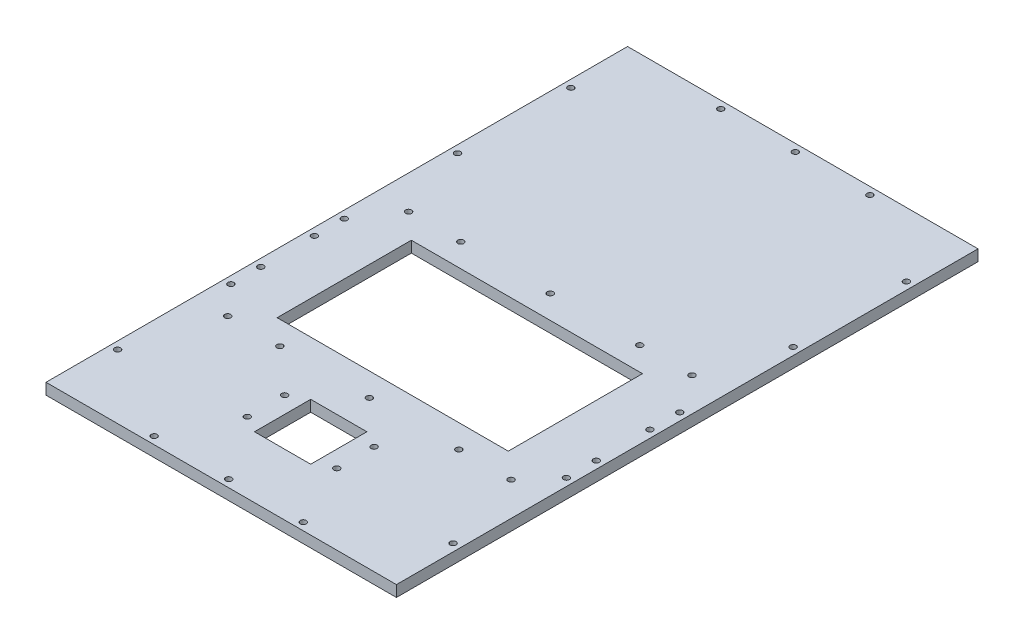
SolidWorks part; units mm, degrees
material "Acrylic (Medium-high impact)"
ref_plane "Front Plane" through (0, 0, 0) normal (0, 0, 1) x (1, 0, 0)
ref_plane "Top Plane" through (0, 0, 0) normal (0, 1, 0) x (1, 0, 0)
ref_plane "Right Plane" through (0, 0, 0) normal (1, 0, 0) x (0, 0, -1)
sketch "Sketch1" plane through (0, 0, 0) normal (0, 1, 0) x (1, 0, 0)
  line L1 (-149.225, -247.65) -> (149.225, -247.65)
  line L2 (-149.225, -247.65) -> (-149.225, 247.65)
  line L3 (-149.225, 247.65) -> (149.225, 247.65)
  line L4 (149.225, -247.65) -> (149.225, 247.65)
  line L5 (-149.225, -247.65) -> (149.225, 247.65) construction
  line L6 (-149.225, 247.65) -> (149.225, -247.65) construction
  line L7 (73.025, -247.65) -> (-130.175, -247.65)
  line L11 (-384.175, -247.65) -> (-231.775, -247.65)
  point P0 (0, 0)
  dimension "D1" = 298.45
  dimension "D2" = 495.3
extrude "Boss-Extrude1" add sketch "Sketch1" along normal mid plane 9.525 contours L1 L4 L3 L2
sketch "Sketch2" [suppressed] plane through (0, 0, 0) normal (0, 1, 0) x (1, 0, 0)
  line L0 (-250.825, -28.575) -> (250.825, -28.575) construction
  line L1 (161.925, -28.575) -> (60.325, -28.575)
  line L2 (161.925, -28.575) -> (161.925, -92.075)
  line L3 (161.925, -92.075) -> (60.325, -92.075)
  line L4 (60.325, -28.575) -> (60.325, -92.075)
  line L5 (0, -5.2388) -> (0, 5.2388) construction
  line L6 (-79.375, -28.575) -> (-168.275, -28.575)
  line L7 (-79.375, -28.575) -> (-79.375, -92.075)
  line L8 (-79.375, -92.075) -> (-168.275, -92.075)
  line L9 (-168.275, -28.575) -> (-168.275, -92.075)
  line L10 (250.825, -28.575) -> (250.825, 28.575) construction
  line L11 (-250.825, -28.575) -> (-250.825, 28.575) construction
  line L12 (-250.825, 28.575) -> (250.825, 28.575) construction
  line L13 (250.825, -28.575) -> (250.825, 28.575) construction
  line L14 (161.925, -28.575) -> (250.825, -28.575)
  line L15 (161.925, -28.575) -> (161.925, -71.755)
  line L16 (161.925, -71.755) -> (250.825, -71.755)
  line L17 (250.825, -28.575) -> (250.825, -71.755)
  line L18 (-250.825, -28.575) -> (-250.825, 28.575) construction
  line L19 (-79.375, -28.575) -> (60.325, -28.575)
  line L20 (-79.375, -28.575) -> (-79.375, -53.975)
  line L21 (-79.375, -53.975) -> (60.325, -53.975)
  line L22 (60.325, -28.575) -> (60.325, -53.975)
  line L23 (-168.275, -28.575) -> (-250.825, -28.575)
  line L24 (-168.275, -28.575) -> (-168.275, -71.755)
  line L25 (-168.275, -71.755) -> (-250.825, -71.755)
  line L26 (-250.825, -28.575) -> (-250.825, -71.755)
  point P19 (60.325, -92.075)
  dimension "D1" = 139.7
  dimension "D2" = 88.9
  dimension "D3" = 82.55
  dimension "D4" = 79.375
  dimension "D5" = 120.65
  dimension "D6" = 43.18
  dimension "D7" = 25.4
  dimension "D8" = 43.18
extrude "Boss-Extrude2" [suppressed] add sketch "Sketch2" along normal mid plane 9.525 contours L6 L9 L8 L7 | L23 L26 L25 L9 | L7 L21 L4 L19 | L17 L14 L2 L16
sketch "Sketch3" plane through (0, 4.7625, 0) normal (0, 1, 0) x (1, 0, 0)
  line L0 (-149.225, 247.65) -> (149.225, 247.65) construction
  line L1 (-98.425, 12.7) -> (98.425, 12.7)
  line L2 (-98.425, 12.7) -> (-98.425, -101.6)
  line L3 (-98.425, -101.6) -> (98.425, -101.6)
  line L4 (98.425, 12.7) -> (98.425, -101.6)
  line L5 (-98.425, 12.7) -> (98.425, -101.6) construction
  line L6 (-98.425, -101.6) -> (98.425, 12.7) construction
  line L7 (-149.225, -247.65) -> (149.225, -247.65) construction
  point P0 (0, -44.45)
  point P7 (0, 247.65)
  point P8 (0, 12.7)
  dimension "D1" = 196.85
  dimension "D2" = 114.3
  dimension "D3" = 203.2
extrude "Cut-Extrude1" cut sketch "Sketch3" against normal through all and the other way through all
sketch "Sketch4" [suppressed] plane through (0, -4.7625, 0) normal (0, -1, 0) x (1, 0, 0)
  line L0 (-107.315, 31.75) -> (107.315, 31.75) construction
  line L1 (-107.315, 33.9979) -> (107.315, 33.9979)
  line L2 (-107.315, 29.5021) -> (107.315, 29.5021)
  line L3 (-107.315, 6.35) -> (107.315, 6.35) construction
  line L4 (-107.315, 8.5979) -> (107.315, 8.5979)
  line L5 (-107.315, 4.1021) -> (107.315, 4.1021)
  arc A0 (-107.315, 33.9979) -> (-107.315, 29.5021) centre (-107.315, 31.75) ccw
  arc A1 (107.315, 29.5021) -> (107.315, 33.9979) centre (107.315, 31.75) ccw
  arc A2 (-107.315, 8.5979) -> (-107.315, 4.1021) centre (-107.315, 6.35) ccw
  arc A3 (107.315, 4.1021) -> (107.315, 8.5979) centre (107.315, 6.35) ccw
  point P0 (-107.315, 31.75)
  point P1 (107.315, 31.75)
  point P3 (107.315, 6.35)
  point P5 (-107.315, 6.35)
  point P10 (0, 31.75)
  point P15 (0, 6.35)
  dimension "D1" = 4.4958
  dimension "D2" = 4.4958
extrude "Cut-Extrude2" [suppressed] cut sketch "Sketch4" against normal through all
sketch "Sketch5" [suppressed] plane through (0, -4.7625, 0) normal (0, -1, 0) x (1, 0, 0)
  line L0 (69.85, 79.375) -> (69.85, -9.525) construction
  line L1 (60.325, 53.975) -> (60.325, 92.075) construction
  line L2 (161.925, 92.075) -> (60.325, 92.075) construction
  line L3 (-247.65, -22.225) -> (247.65, -22.225) construction
  line L4 (69.85, 79.375) -> (69.85, -9.525) construction
  line L5 (72.0979, 79.375) -> (72.0979, -9.525)
  line L6 (67.6021, 79.375) -> (67.6021, -9.525)
  line L7 (-88.9, 79.375) -> (-88.9, -9.525) construction
  line L8 (-79.375, 53.975) -> (-79.375, 92.075) construction
  line L9 (-79.375, 92.075) -> (-168.275, 92.075) construction
  line L10 (-88.9, 79.375) -> (-88.9, -9.525) construction
  line L11 (-86.6521, 79.375) -> (-86.6521, -9.525)
  line L12 (-91.1479, 79.375) -> (-91.1479, -9.525)
  arc A0 (72.0979, 79.375) -> (67.6021, 79.375) centre (69.85, 79.375) ccw
  arc A1 (67.6021, -9.525) -> (72.0979, -9.525) centre (69.85, -9.525) ccw
  arc A2 (-86.6521, 79.375) -> (-91.1479, 79.375) centre (-88.9, 79.375) ccw
  arc A3 (-91.1479, -9.525) -> (-86.6521, -9.525) centre (-88.9, -9.525) ccw
  point P8 (69.85, 34.925)
  point P19 (-88.9, 34.925)
  dimension "D1" = 9.525
  dimension "D2" = 12.7
  dimension "D3" = 12.7
  dimension "D4" = 4.4958
  dimension "D5" = 9.525
  dimension "D6" = 12.7
  dimension "D7" = 12.7
  dimension "D8" = 4.4958
extrude "Cut-Extrude3" [suppressed] cut sketch "Sketch5" against normal through all contours L12 A3 L11 A2 | L6 A1 L5 A0
sketch "Sketch6" [suppressed] plane through (0, 4.7625, 0) normal (0, 1, 0) x (1, 0, 0)
  line L0 (-79.375, -38.1) -> (-79.375, 38.1) construction
  line L1 (-88.9, -50.8) -> (-88.9, 50.8) construction
  line L2 (-88.9, -50.8) -> (88.9, -50.8) construction
  line L3 (-88.9, 50.8) -> (88.9, 50.8) construction
  line L4 (79.375, -38.1) -> (79.375, 38.1) construction
  line L5 (88.9, -50.8) -> (88.9, 50.8) construction
  line L6 (-79.375, -38.1) -> (-79.375, 38.1) construction
  line L7 (-81.6229, -38.1) -> (-81.6229, 38.1)
  line L8 (-77.1271, -38.1) -> (-77.1271, 38.1)
  line L9 (79.375, -38.1) -> (79.375, 38.1) construction
  line L10 (77.1271, -38.1) -> (77.1271, 38.1)
  line L11 (81.6229, -38.1) -> (81.6229, 38.1)
  arc A0 (-81.6229, -38.1) -> (-77.1271, -38.1) centre (-79.375, -38.1) ccw
  arc A1 (-77.1271, 38.1) -> (-81.6229, 38.1) centre (-79.375, 38.1) ccw
  arc A2 (77.1271, -38.1) -> (81.6229, -38.1) centre (79.375, -38.1) ccw
  arc A3 (81.6229, 38.1) -> (77.1271, 38.1) centre (79.375, 38.1) ccw
  point P12 (-79.375, 0)
  point P17 (79.375, 0)
  dimension "D1" = 9.525
  dimension "D2" = 12.7
  dimension "D3" = 12.7
  dimension "D4" = 9.525
  dimension "D5" = 12.7
  dimension "D6" = 12.7
  dimension "D7" = 4.4958
  dimension "D8" = 4.4958
extrude "Cut-Extrude4" [suppressed] cut sketch "Sketch6" against normal through all
sketch "Sketch7" [suppressed] plane through (0, 4.7625, 0) normal (0, 1, 0) x (1, 0, 0)
  point P0 (115.1313, 66.802)
  point P1 (139.827, 42.1063)
  point P3 (-139.827, 42.1063)
  point P5 (-115.1313, 66.802)
hole_wizard "#12 Clearance Hole1" [suppressed] positions "Sketch8" profile "Sketch9" hole size "#12" standard "ANSI Inch"
sketch "Sketch8" plane through (0, 4.7625, 0) normal (0, 1, 0) x (1, 0, 0)
  point P0 (-139.827, 42.1063)
  point P3 (-115.1313, 66.802)
  point P6 (115.1313, 66.802)
  point P9 (139.827, 42.1063)
sketch "Sketch9" plane through (-139.827, 4.7625, -42.1063) normal (1, 0, 0) x (0, 0, 1)
  line L0 (0, 0) -> (0, 18.1964)
  line L1 (0, 18.1964) -> (2.8067, 16.51)
  line L2 (2.8067, 16.51) -> (2.8067, 0)
  line L5 (2.8067, 0) -> (0, 0)
  line L10 (0, 18.1964) -> (-2.8067, 16.51) construction
  line L11 (0, -6.35) -> (0, 107.95) construction
  dimension "Hole Dia." = 5.6134
  dimension "Hole Depth" = 16.51
  dimension "Drill Angle" = 118
sketch "Sketch10" [suppressed] plane through (0, -4.7625, 0) normal (0, -1, 0) x (1, 0, 0)
  point P0 (223.8375, -6.35)
  point P1 (223.8375, 19.05)
  point P3 (-223.8375, 19.05)
  point P5 (-223.8375, -6.35)
hole_wizard "#12 Clearance Hole3" [suppressed] positions "Sketch11" profile "Sketch12" hole size "#12" standard "ANSI Inch"
sketch "Sketch11" plane through (0, -4.7625, 0) normal (0, -1, 0) x (-1, 0, 0)
  point P0 (-223.8375, -19.05)
  point P3 (-223.8375, 6.35)
  point P6 (223.8375, -19.05)
  point P9 (223.8375, 6.35)
sketch "Sketch12" plane through (223.8375, -4.7625, 19.05) normal (1, 0, 0) x (0, 0, -1)
  line L0 (0, 0) -> (0, 18.1964)
  line L1 (0, 18.1964) -> (2.8067, 16.51)
  line L2 (2.8067, 16.51) -> (2.8067, 0)
  line L5 (2.8067, 0) -> (0, 0)
  line L10 (0, 18.1964) -> (-2.8067, 16.51) construction
  line L11 (0, -6.35) -> (0, 107.95) construction
  dimension "Hole Dia." = 5.6134
  dimension "Hole Depth" = 16.51
  dimension "Drill Angle" = 118
sketch "Sketch13" [suppressed] plane through (0, -4.7625, 0) normal (0, -1, 0) x (1, 0, 0)
  point P0 (133.35, -223.8375)
  point P1 (107.95, -223.8375)
  point P3 (-107.95, -223.8375)
  point P5 (-133.35, -223.8375)
  point P7 (133.35, 223.8375)
  point P9 (107.95, 223.8375)
  point P11 (-107.95, 223.8375)
  point P13 (-133.35, 223.8375)
hole_wizard "#12 Clearance Hole2" [suppressed] positions "Sketch14" profile "Sketch15" hole size "#12" standard "ANSI Inch"
sketch "Sketch14" [suppressed] plane through (0, -4.7625, 0) normal (0, -1, 0) x (-1, 0, 0)
  point P0 (107.95, -223.8375)
  point P3 (133.35, -223.8375)
  point P6 (133.35, 223.8375)
  point P9 (107.95, 223.8375)
  point P12 (-133.35, 223.8375)
  point P15 (-107.95, 223.8375)
  point P18 (-133.35, -223.8375)
  point P21 (-107.95, -223.8375)
sketch "Sketch15" plane through (-107.95, -4.7625, 223.8375) normal (1, 0, 0) x (0, 0, -1)
  line L0 (0, 0) -> (0, 18.1964)
  line L1 (0, 18.1964) -> (2.8067, 16.51)
  line L2 (2.8067, 16.51) -> (2.8067, 0)
  line L5 (2.8067, 0) -> (0, 0)
  line L10 (0, 18.1964) -> (-2.8067, 16.51) construction
  line L11 (0, -6.35) -> (0, 107.95) construction
  dimension "Hole Dia." = 5.6134
  dimension "Hole Depth" = 16.51
  dimension "Drill Angle" = 118
sketch "Sketch16" [suppressed] plane through (0, 4.7625, 0) normal (0, 1, 0) x (1, 0, 0)
  line L0 (88.9, -50.8) -> (88.9, 50.8) construction
  line L1 (-88.9, -50.8) -> (-88.9, 50.8) construction
  line L2 (-88.9, -50.8) -> (88.9, -50.8) construction
  point P0 (79.375, -38.1)
  point P1 (-79.375, -38.1)
  dimension "D1" = 9.525
  dimension "D2" = 9.525
  dimension "D3" = 12.7
hole_wizard "#8 Clearance Hole1" [suppressed] positions "Sketch17" profile "Sketch19" hole size "#8" standard "ANSI Inch"
sketch "Sketch17" plane through (0, 4.7625, 0) normal (0, 1, 0) x (1, 0, 0)
  point P0 (79.375, -38.1)
  point P3 (-79.375, -38.1)
sketch "Sketch19" plane through (79.375, 4.7625, 38.1) normal (1, 0, 0) x (0, 0, 1)
  line L0 (0, 0) -> (0, 12.0187)
  line L1 (0, 12.0187) -> (2.2479, 10.668)
  line L2 (2.2479, 10.668) -> (2.2479, 0)
  line L5 (2.2479, 0) -> (0, 0)
  line L10 (0, 12.0187) -> (-2.2479, 10.668) construction
  line L11 (0, -6.35) -> (0, 107.95) construction
  dimension "Hole Dia." = 4.4958
  dimension "Hole Depth" = 10.668
  dimension "Drill Angle" = 118
sketch "Sketch20" plane through (0, -4.7625, 0) normal (0, -1, 0) x (1, 0, 0)
  line L0 (-149.225, 247.65) -> (149.225, 247.65) construction
  line L1 (23.9395, 147.5105) -> (-23.9395, 147.5105)
  line L2 (23.9395, 147.5105) -> (23.9395, 195.3895)
  line L3 (23.9395, 195.3895) -> (-23.9395, 195.3895)
  line L4 (-23.9395, 147.5105) -> (-23.9395, 195.3895)
  line L5 (23.9395, 147.5105) -> (-23.9395, 195.3895) construction
  line L6 (23.9395, 195.3895) -> (-23.9395, 147.5105) construction
  line L8 (38.1, 155.575) -> (-38.1, 155.575) construction
  line L9 (38.1, 155.575) -> (38.1, 187.325) construction
  line L10 (38.1, 187.325) -> (-38.1, 187.325) construction
  line L11 (-38.1, 155.575) -> (-38.1, 187.325) construction
  point P0 (0, 171.45)
  point P7 (0, 247.65)
  point P8 (38.1, 155.575)
  point P9 (38.1, 187.325)
  point P10 (-38.1, 155.575)
  point P11 (-38.1, 187.325)
  point P18 (0, 187.325)
  point P19 (0, 195.3895)
  point P20 (-38.1, 171.45)
  point P21 (-23.9395, 171.45)
  dimension "D1" = 47.879
  dimension "D2" = 47.879
  dimension "D3" = 38.1
  dimension "D4" = 15.875
  dimension "D5" = 76.2
extrude "Cut-Extrude5" cut sketch "Sketch20" against normal through all contours L1 L4 L3 L2
hole_wizard "#10 Clearance Hole1" positions "Sketch21" profile "Sketch22" hole size "#10" standard "ANSI Inch"
sketch "Sketch21" plane through (0, -4.7625, 0) normal (0, -1, 0) x (-1, 0, 0)
  point P0 (-38.1, -155.575)
  point P3 (38.1, -155.575)
  point P6 (38.1, -187.325)
  point P9 (-38.1, -187.325)
sketch "Sketch22" plane through (38.1, -4.7625, 155.575) normal (1, 0, 0) x (0, 0, -1)
  line L0 (0, 0) -> (0, 12.2018)
  line L1 (0, 12.2018) -> (2.5527, 10.668)
  line L2 (2.5527, 10.668) -> (2.5527, 0)
  line L5 (2.5527, 0) -> (0, 0)
  line L10 (0, 12.2018) -> (-2.5527, 10.668) construction
  line L11 (0, -6.35) -> (0, 107.95) construction
  dimension "Hole Dia." = 5.1054
  dimension "Hole Depth" = 10.668
  dimension "Drill Angle" = 118
sketch "Sketch23" [suppressed] plane through (-250.825, 0, 0) normal (-1, 0, 0) x (0, 0, 1)
  line L4 (-28.575, -4.7625) -> (71.755, -4.7625)
  line L5 (71.755, -4.7625) -> (71.755, 4.7625)
  line L6 (71.755, 4.7625) -> (-28.575, 4.7625)
  line L7 (-28.575, 4.7625) -> (-28.575, -4.7625)
  line L8 (-28.575, -4.7625) -> (71.755, -4.7625)
  line L9 (71.755, -4.7625) -> (71.755, 4.7625)
  line L10 (71.755, 4.7625) -> (-28.575, 4.7625)
  line L11 (-28.575, 4.7625) -> (-28.575, -4.7625)
  dimension "D1" = 0
extrude "Boss-Extrude3" [suppressed] add sketch "Sketch23" along normal blind 6.35
mirror "Mirror1" [suppressed] about plane through (0, 0, 0) normal (1, 0, 0)
sketch "Sketch27" [suppressed] plane through (0, 4.7625, 0) normal (0, 1, 0) x (1, 0, 0)
  line L1 (257.175, -71.755) -> (257.175, 28.575) construction
  line L2 (-257.175, 28.575) -> (257.175, 28.575) construction
  point P0 (241.3, 12.7)
  dimension "D1" = 15.875
  dimension "D2" = 15.875
hole_wizard "#10 Clearance Hole2" [suppressed] positions "Sketch28" profile "Sketch30" hole size "#10" standard "ANSI Inch"
sketch "Sketch28" plane through (0, 4.7625, 0) normal (0, 1, 0) x (1, 0, 0)
  point P0 (241.3, 12.7)
sketch "Sketch30" plane through (241.3, 4.7625, -12.7) normal (1, 0, 0) x (0, 0, 1)
  line L0 (0, 0) -> (0, 9.525)
  line L1 (0, 9.525) -> (2.5527, 9.525)
  line L2 (2.5527, 9.525) -> (2.5527, 0)
  line L5 (2.5527, 0) -> (0, 0)
  line L11 (0, -6.35) -> (0, 107.95) construction
  dimension "Thru Hole Dia." = 5.1054
  dimension "Thru Hole Depth" = 9.525
pattern_linear "LPattern1" [suppressed] count 6 spacing 96.52
sketch "Sketch31" [suppressed] plane through (0, 4.7625, 0) normal (0, 1, 0) x (1, 0, 0)
  line L1 (0, -5.2388) -> (0, 5.2388) construction
  line L2 (-149.225, 76.2) -> (149.225, 76.2) construction
  point P0 (-95.25, 60.325)
  dimension "D1" = 15.875
  dimension "D2" = 95.25
hole_wizard "#10 Clearance Hole3" [suppressed] positions "Sketch32" profile "Sketch33" hole size "#10" standard "ANSI Inch"
sketch "Sketch32" plane through (0, 4.7625, 0) normal (0, 1, 0) x (1, 0, 0)
  point P0 (-95.25, 60.325)
sketch "Sketch33" plane through (-95.25, 4.7625, -60.325) normal (1, 0, 0) x (0, 0, 1)
  line L0 (0, 0) -> (0, 9.525)
  line L1 (0, 9.525) -> (2.5527, 9.525)
  line L2 (2.5527, 9.525) -> (2.5527, 0)
  line L5 (2.5527, 0) -> (0, 0)
  line L11 (0, -6.35) -> (0, 107.95) construction
  dimension "Thru Hole Dia." = 5.1054
  dimension "Thru Hole Depth" = 9.525
pattern_linear "LPattern2" [suppressed] count 4 spacing 63.5
sketch "Sketch34" plane through (0, 4.7625, 0) normal (0, 1, 0) x (1, 0, 0)
  line L0 (0, -5.2388) -> (0, 5.2388) construction
  line L1 (-149.225, 247.65) -> (149.225, 247.65) construction
  point P0 (-63.5, 241.3)
  dimension "D1" = 63.5
  dimension "D2" = 6.35
hole_wizard "#10 Clearance Hole4" positions "Sketch35" profile "Sketch36" hole size "#10" standard "ANSI Inch" end condition up to next
sketch "Sketch35" plane through (0, 4.7625, 0) normal (0, 1, 0) x (1, 0, 0)
  point P0 (-63.5, 241.3)
sketch "Sketch36" plane through (-63.5, 4.7625, -241.3) normal (1, 0, 0) x (0, 0, 1)
  line L0 (0, 0) -> (0, 9.525)
  line L1 (0, 9.525) -> (2.5527, 9.525)
  line L2 (2.5527, 9.525) -> (2.5527, 0)
  line L5 (2.5527, 0) -> (0, 0)
  line L11 (0, -6.35) -> (0, 107.95) construction
  dimension "Thru Hole Dia." = 5.1054
  dimension "Thru Hole Depth" = 9.525
pattern_linear "LPattern3" count 3 spacing 63.5 along (1, 0, 0) of "#10 Clearance Hole4"
mirror "Mirror2" about plane through (0, 0, 0) normal (0, 0, 1) of "LPattern3", "#10 Clearance Hole4"
sketch "Sketch37" plane through (0, 4.7625, 0) normal (0, 1, 0) x (1, 0, 0)
  line L0 (-5.2388, 0) -> (5.2388, 0) construction
  line L1 (-149.225, -247.65) -> (-149.225, 247.65) construction
  point P0 (-142.875, 0)
  dimension "D1" = 6.35
hole_wizard "#10 Clearance Hole5" positions "Sketch38" profile "Sketch39" hole size "#10" standard "ANSI Inch" end condition up to next
sketch "Sketch38" plane through (0, 4.7625, 0) normal (0, 1, 0) x (1, 0, 0)
  point P0 (-142.875, 0)
sketch "Sketch39" plane through (-142.875, 4.7625, 0) normal (1, 0, 0) x (0, 0, 1)
  line L0 (0, 0) -> (0, 9.525)
  line L1 (0, 9.525) -> (2.5527, 9.525)
  line L2 (2.5527, 9.525) -> (2.5527, 0)
  line L5 (2.5527, 0) -> (0, 0)
  line L11 (0, -6.35) -> (0, 107.95) construction
  dimension "Thru Hole Dia." = 5.1054
  dimension "Thru Hole Depth" = 9.525
pattern_linear "LPattern4" count 3 spacing 96.52 along (0, 0, -1) count 3 spacing 96.52 along (0, 0, 1) of "#10 Clearance Hole5"
mirror "Mirror3" about plane through (0, 0, 0) normal (1, 0, 0) of "LPattern4", "#10 Clearance Hole5"
sketch "Sketch40" [suppressed] plane through (0, 4.7625, 0) normal (0, 1, 0) x (1, 0, 0)
  line L0 (-79.375, -53.975) -> (-79.375, -92.075) construction
  line L3 (-88.9, -79.375) -> (-88.9, -9.525) construction
  line L4 (-91.1479, -79.375) -> (-91.1479, -9.525)
  line L5 (-86.6521, -79.375) -> (-86.6521, -9.525)
  line L6 (69.85, -79.375) -> (69.85, -9.525) construction
  line L7 (67.6021, -79.375) -> (67.6021, -9.525)
  line L8 (72.0979, -79.375) -> (72.0979, -9.525)
  line L9 (60.325, -53.975) -> (60.325, -92.075) construction
  line L12 (-79.375, -92.075) -> (-168.275, -92.075) construction
  line L13 (161.925, -92.075) -> (60.325, -92.075) construction
  arc A2 (-91.1479, -79.375) -> (-86.6521, -79.375) centre (-88.9, -79.375) ccw
  arc A3 (-86.6521, -9.525) -> (-91.1479, -9.525) centre (-88.9, -9.525) ccw
  arc A4 (67.6021, -79.375) -> (72.0979, -79.375) centre (69.85, -79.375) ccw
  arc A5 (72.0979, -9.525) -> (67.6021, -9.525) centre (69.85, -9.525) ccw
  point P7 (-88.9, -44.45)
  point P14 (69.85, -44.45)
  dimension "D1" = 9.525
  dimension "D2" = 4.4958
  dimension "D3" = 4.4958
  dimension "D4" = 9.525
  dimension "D5" = 12.7
  dimension "D6" = 12.7
  dimension "D7" = 69.85
  dimension "D8" = 69.85
extrude "Cut-Extrude6" [suppressed] cut sketch "Sketch40" against normal up to next
sketch "Sketch41" plane through (0, -4.7625, 0) normal (0, -1, 0) x (1, 0, 0)
  point P0 (120.65, -32.5755)
  point P1 (-120.65, -32.5755)
  point P3 (-120.65, 121.4755)
  point P5 (120.65, 121.4755)
hole_wizard "#10 Clearance Hole6" positions "Sketch42" profile "Sketch43" hole size "#10" standard "ANSI Inch" end condition through all
sketch "Sketch42" plane through (0, 4.7625, 0) normal (0, 1, 0) x (1, 0, 0)
  point P0 (120.65, 32.5755)
  point P3 (120.65, -121.4755)
  point P6 (-120.65, -121.4755)
  point P9 (-120.65, 32.5755)
sketch "Sketch43" plane through (120.65, 4.7625, -32.5755) normal (1, 0, 0) x (0, 0, 1)
  line L0 (0, 0) -> (0, 9.525)
  line L1 (0, 9.525) -> (2.5527, 9.525)
  line L2 (2.5527, 9.525) -> (2.5527, 0)
  line L5 (2.5527, 0) -> (0, 0)
  line L11 (0, -6.35) -> (0, 107.95) construction
  dimension "Thru Hole Dia." = 5.1054
  dimension "Thru Hole Depth" = 9.525
sketch "Sketch44" plane through (0, 4.7625, 0) normal (0, 1, 0) x (1, 0, 0)
  line L0 (0, -5.2388) -> (0, 5.2388) construction
  line L2 (120.65, 32.5755) -> (-120.65, 32.5755) construction
  line L3 (120.65, -121.4755) -> (-120.65, -121.4755) construction
  point P0 (76.2, 32.5755)
  point P1 (0, 32.5755)
  point P2 (-76.2, 32.5755)
  point P3 (76.2, -121.4755)
  point P4 (0, -121.4755)
  point P5 (-76.2, -121.4755)
  dimension "D1" = 76.2
  dimension "D2" = 76.2
hole_wizard "#10 Clearance Hole7" positions "Sketch45" profile "Sketch46" hole size "#10" standard "ANSI Inch" end condition through all
sketch "Sketch45" plane through (0, 4.7625, 0) normal (0, 1, 0) x (1, 0, 0)
  point P0 (76.2, 32.5755)
  point P3 (0, 32.5755)
  point P6 (-76.2, 32.5755)
  point P9 (76.2, -121.4755)
  point P12 (0, -121.4755)
  point P15 (-76.2, -121.4755)
sketch "Sketch46" plane through (76.2, 4.7625, -32.5755) normal (1, 0, 0) x (0, 0, 1)
  line L0 (0, 0) -> (0, 9.525)
  line L1 (0, 9.525) -> (2.5527, 9.525)
  line L2 (2.5527, 9.525) -> (2.5527, 0)
  line L5 (2.5527, 0) -> (0, 0)
  line L11 (0, -6.35) -> (0, 107.95) construction
  dimension "Thru Hole Dia." = 5.1054
  dimension "Thru Hole Depth" = 9.525
sketch "Sketch47" plane through (0, 4.7625, 0) normal (0, 1, 0) x (1, 0, 0)
  line L1 (-142.875, 0) -> (-142.875, -96.52) construction
  line L2 (142.875, 0) -> (142.875, -96.52) construction
  point P0 (-142.875, -71.12)
  point P1 (142.875, -25.4)
  point P2 (-142.875, -25.4)
  point P3 (142.875, -71.12)
  dimension "D1" = 25.4
  dimension "D2" = 25.4
  dimension "D3" = 25.4
  dimension "D4" = 25.4
hole_wizard "#10 Clearance Hole8" positions "Sketch48" profile "Sketch49" hole size "#10" standard "ANSI Inch" end condition through all
sketch "Sketch48" plane through (0, 4.7625, 0) normal (0, 1, 0) x (1, 0, 0)
  point P0 (-142.875, -71.12)
  point P3 (142.875, -25.4)
  point P7 (-142.875, -25.4)
  point P10 (142.875, -71.12)
sketch "Sketch49" plane through (-142.875, 4.7625, 71.12) normal (1, 0, 0) x (0, 0, 1)
  line L0 (0, 0) -> (0, 9.525)
  line L1 (0, 9.525) -> (2.5527, 9.525)
  line L2 (2.5527, 9.525) -> (2.5527, 0)
  line L5 (2.5527, 0) -> (0, 0)
  line L11 (0, -6.35) -> (0, 107.95) construction
  dimension "Thru Hole Dia." = 5.1054
  dimension "Thru Hole Depth" = 9.525
sketch "Sketch50" [suppressed] plane through (0, 0, 0) normal (0, 1, 0) x (1, 0, 0)
  line L1 (-209.55, -50.8) -> (209.55, -50.8)
  line L2 (-209.55, -50.8) -> (-209.55, 50.8)
  line L3 (-209.55, 50.8) -> (209.55, 50.8)
  line L4 (209.55, -50.8) -> (209.55, 50.8)
  line L5 (-209.55, -50.8) -> (209.55, 50.8) construction
  line L6 (-209.55, 50.8) -> (209.55, -50.8) construction
  point P0 (0, 0)
  dimension "D1" = 419.1
  dimension "D2" = 101.6
extrude "Boss-Extrude4" [suppressed] add sketch "Sketch50" along normal blind 9.525
sketch "Sketch51" [suppressed] plane through (0, 0, 0) normal (0, -1, 0) x (1, 0, 0)
  line L0 (144.78, -12.7) -> (144.78, -50.8) construction
  line L1 (152.7175, -12.7) -> (152.7175, -50.8)
  line L2 (136.8425, -12.7) -> (136.8425, -50.8)
  line L3 (209.55, -50.8) -> (-209.55, -50.8) construction
  line L4 (209.55, 50.8) -> (209.55, -50.8) construction
  line L5 (48.26, -50.8) -> (48.26, -12.7) construction
  line L7 (40.3225, -50.8) -> (40.3225, -12.7)
  line L8 (56.1975, -50.8) -> (56.1975, -12.7)
  arc A0 (152.7175, -12.7) -> (136.8425, -12.7) centre (144.78, -12.7) ccw
  arc A1 (136.8425, -50.8) -> (152.7175, -50.8) centre (144.78, -50.8) ccw
  arc A2 (40.3225, -50.8) -> (56.1975, -50.8) centre (48.26, -50.8) ccw
  arc A3 (56.1975, -12.7) -> (40.3225, -12.7) centre (48.26, -12.7) ccw
  point P2 (144.78, -31.75)
  point P7 (48.26, -31.75)
  dimension "D1" = 38.1
  dimension "D2" = 64.77
  dimension "D3" = 15.875
  dimension "D4" = 15.875
  dimension "D5" = 96.52
extrude "Cut-Extrude7" [suppressed] cut sketch "Sketch51" against normal up to next
mirror "Mirror4" [suppressed] about plane through (0, 0, 0) normal (1, 0, 0)
sketch "Sketch52" [suppressed] plane through (0, 4.7625, 0) normal (0, 1, 0) x (1, 0, 0)
  line L0 (-79.375, -92.075) -> (-168.275, -92.075) construction
  line L1 (161.925, -92.075) -> (60.325, -92.075) construction
  point P0 (-123.825, -38.1)
  point P1 (111.125, -38.1)
  point P4 (-123.825, -92.075)
  point P7 (111.125, -92.075)
  dimension "D1" = 53.975
hole_wizard "#10 Clearance Hole9" [suppressed] positions "Sketch53" profile "Sketch54" hole size "#10" standard "ANSI Inch"
sketch "Sketch53" plane through (0, 4.7625, 0) normal (0, 1, 0) x (1, 0, 0)
  point P0 (-123.825, -38.1)
  point P3 (111.125, -38.1)
sketch "Sketch54" plane through (-123.825, 4.7625, 38.1) normal (1, 0, 0) x (0, 0, 1)
  line L0 (0, 0) -> (0, 9.525)
  line L1 (0, 9.525) -> (2.5527, 9.525)
  line L2 (2.5527, 9.525) -> (2.5527, 0)
  line L5 (2.5527, 0) -> (0, 0)
  line L11 (0, -6.35) -> (0, 107.95) construction
  dimension "Thru Hole Dia." = 5.1054
  dimension "Thru Hole Depth" = 9.525
sketch "Sketch55" [suppressed] plane through (0, 0, 0) normal (0, -1, 0) x (1, 0, 0)
  line L0 (111.125, 34.925) -> (111.125, -34.925) construction
  line L1 (113.792, 34.925) -> (113.792, -34.925)
  line L2 (108.458, 34.925) -> (108.458, -34.925)
  line L3 (-123.825, 34.925) -> (-123.825, -34.925) construction
  line L4 (209.55, 50.8) -> (209.55, -50.8) construction
  line L5 (-121.158, 34.925) -> (-121.158, -34.925)
  line L6 (-126.492, 34.925) -> (-126.492, -34.925)
  line L7 (-209.55, -50.8) -> (-209.55, 50.8) construction
  arc A0 (113.792, 34.925) -> (108.458, 34.925) centre (111.125, 34.925) ccw
  arc A1 (108.458, -34.925) -> (113.792, -34.925) centre (111.125, -34.925) ccw
  arc A2 (-121.158, 34.925) -> (-126.492, 34.925) centre (-123.825, 34.925) ccw
  arc A3 (-126.492, -34.925) -> (-121.158, -34.925) centre (-123.825, -34.925) ccw
  point P2 (111.125, 0)
  point P11 (209.55, 0)
  point P12 (-123.825, 0)
  dimension "D1" = 5.334
  dimension "D2" = 69.85
  dimension "D3" = 98.425
  dimension "D4" = 85.725
  dimension "D5" = 5.334
  dimension "D6" = 69.85
extrude "Cut-Extrude8" [suppressed] cut sketch "Sketch55" against normal up to next contours L6 A3 L5 A2 | L2 A1 L1 A0
sketch "Sketch56" [suppressed] plane through (0, 4.7625, 0) normal (0, 1, 0) x (1, 0, 0)
  line L0 (-257.175, -71.755) -> (-257.175, 28.575) construction
  line L1 (-168.275, -71.755) -> (-257.175, -71.755) construction
  line L2 (257.175, -71.755) -> (257.175, 28.575) construction
  line L3 (161.925, -71.755) -> (257.175, -71.755) construction
  point P0 (-234.95, -62.23)
  point P5 (234.95, -62.23)
  dimension "D1" = 22.225
  dimension "D2" = 9.525
  dimension "D3" = 22.225
  dimension "D4" = 9.525
hole_wizard "#10-32 Tapped Hole2" [suppressed] positions "Sketch57" profile "Sketch58" tap size "#10-32" standard "ANSI Inch"
sketch "Sketch57" plane through (0, 4.7625, 0) normal (0, 1, 0) x (1, 0, 0)
  point P0 (234.95, -62.23)
  point P3 (-234.95, -62.23)
sketch "Sketch58" plane through (234.95, 4.7625, 62.23) normal (1, 0, 0) x (0, 0, 1)
  line L0 (0, 0) -> (0, 9.525)
  line L1 (0, 9.525) -> (2.0193, 9.525)
  line L2 (2.0193, 9.525) -> (2.0193, 0)
  line L5 (2.0193, 0) -> (0, 0)
  line L11 (0, -6.35) -> (0, 107.95) construction
  dimension "Thru Tap Drill Dia." = 4.0386
  dimension "Thru Tap Drill Depth" = 9.525
sketch "Sketch59" [suppressed] plane through (0, 4.7625, 0) normal (0, 1, 0) x (1, 0, 0)
  line L0 (-149.225, -76.2) -> (149.225, -76.2) construction
  line L1 (149.225, -76.2) -> (149.225, 76.2) construction
  line L2 (-149.225, -76.2) -> (-149.225, 76.2) construction
  point P0 (139.7, -14.605)
  point P1 (-139.7, -14.605)
  dimension "D1" = 61.595
  dimension "D2" = 9.525
  dimension "D3" = 9.525
hole_wizard "#10-32 Tapped Hole1" [suppressed] positions "Sketch60" profile "Sketch62" tap size "#10-32" standard "ANSI Inch"
sketch "Sketch60" plane through (0, 4.7625, 0) normal (0, 1, 0) x (1, 0, 0)
  point P0 (-139.7, -14.605)
  point P3 (139.7, -14.605)
sketch "Sketch62" plane through (-139.7, 4.7625, 14.605) normal (1, 0, 0) x (0, 0, 1)
  line L0 (0, 0) -> (0, 9.525)
  line L1 (0, 9.525) -> (2.0193, 9.525)
  line L2 (2.0193, 9.525) -> (2.0193, 0)
  line L5 (2.0193, 0) -> (0, 0)
  line L11 (0, -6.35) -> (0, 107.95) construction
  dimension "Thru Tap Drill Dia." = 4.0386
  dimension "Thru Tap Drill Depth" = 9.525
cosmetic thread "Hole Thread1" [suppressed] parameters "D2"=4.826
cosmetic thread "Hole Thread2" [suppressed] parameters "D2"=4.826
sketch "Sketch63" [suppressed] plane through (0, 4.7625, 0) normal (0, 1, 0) x (1, 0, 0)
  line L0 (-149.225, 76.2) -> (149.225, 76.2) construction
  line L1 (-149.225, -76.2) -> (-149.225, 76.2) construction
  point P0 (-65.0875, 19.05)
  point P1 (-26.9875, 19.05)
  dimension "D1" = 38.1
  dimension "D2" = 57.15
  dimension "D3" = 84.1375
hole_wizard "1/4 Clearance Hole1" [suppressed] positions "Sketch64" profile "Sketch65" hole size "1/4" standard "ANSI Inch"
sketch "Sketch64" plane through (0, 4.7625, 0) normal (0, 1, 0) x (1, 0, 0)
  point P0 (-65.0875, 19.05)
  point P3 (-26.9875, 19.05)
sketch "Sketch65" plane through (-65.0875, 4.7625, -19.05) normal (1, 0, 0) x (0, 0, 1)
  line L0 (0, 0) -> (0, 9.525)
  line L1 (0, 9.525) -> (3.3782, 9.525)
  line L2 (3.3782, 9.525) -> (3.3782, 0)
  line L5 (3.3782, 0) -> (0, 0)
  line L11 (0, -6.35) -> (0, 107.95) construction
  dimension "Thru Hole Dia." = 6.7564
  dimension "Thru Hole Depth" = 9.525
mirror "Mirror5" [suppressed] about plane through (0, 0, 0) normal (1, 0, 0)
